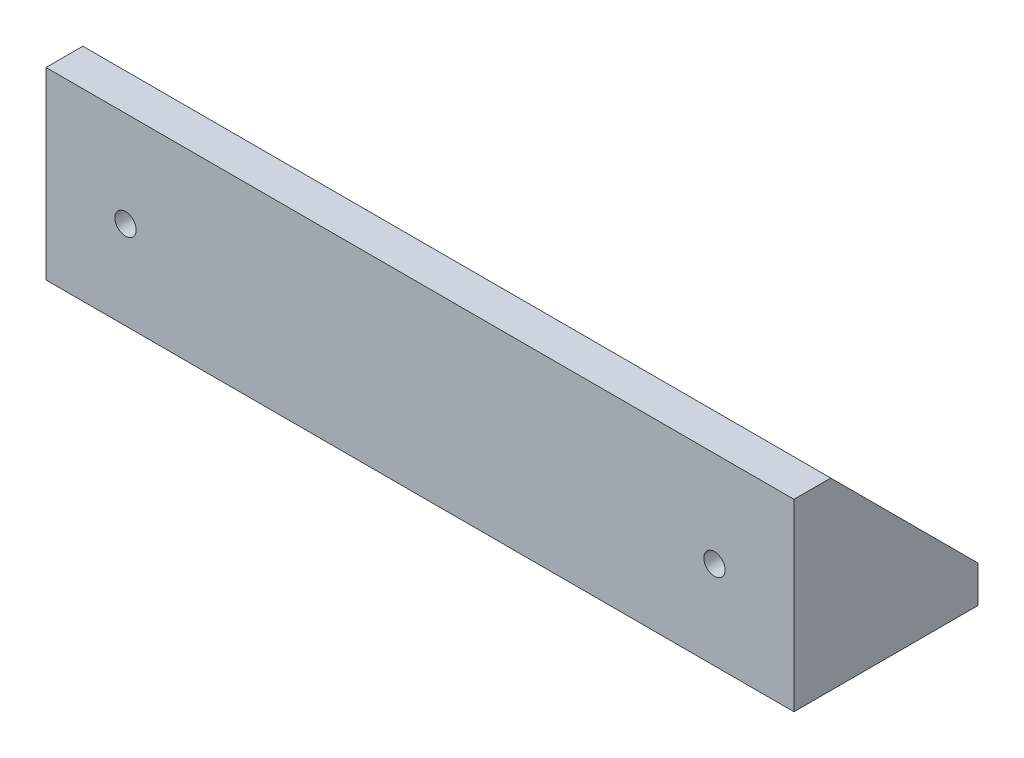
SolidWorks part; units mm, degrees
ref_plane "Front Plane" through (0, 0, 0) normal (0, 0, 1) x (1, 0, 0)
ref_plane "Top Plane" through (0, 0, 0) normal (0, 1, 0) x (1, 0, 0)
ref_plane "Right Plane" through (0, 0, 0) normal (1, 0, 0) x (0, 0, -1)
sketch "Sketch1" plane through (0, 0, 0) normal (1, 0, 0) x (0, 0, -1)
  line L0 (0, 25) -> (0, 0)
  line L1 (0, 0) -> (25, 0)
  line L2 (25, 0) -> (25, 5)
  line L3 (25, 5) -> (5, 25)
  line L4 (5, 25) -> (0, 25)
  point P3 (0, 0)
  point P7 (0, 0)
  dimension "D1" = 25
  dimension "D2" = 5
extrude "Boss-Extrude1" add sketch "Sketch1" along normal blind 101.6 from offset 50.8 offset against normal yes
sketch "Sketch3" plane through (0, 0, 0) normal (1, 0, 0) x (0, 0, -1)
  line L1 (5, 25) -> (25, 25)
  line L2 (5, 25) -> (5, 5)
  line L3 (5, 5) -> (25, 5)
  line L4 (25, 25) -> (25, 5)
  point P4 (0, 0)
  point P5 (0, 0)
  point P8 (0, 0)
  point P9 (0, 0)
  point P11 (0, 0)
  point P12 (0, 0)
  point P14 (0, 0)
  point P15 (0, 0)
  point P16 (0, 0)
  point P17 (0, 0)
  point P18 (0, 0)
  point P19 (0, 0)
  point P21 (0, 0)
extrude "hollow" cut sketch "Sketch3" against normal blind 90 from offset 45
hole_wizard "bottom holes" positions "Sketch4" profile "Sketch5" hole size "M2.5" standard "ISO" end condition through all
sketch "Sketch4" plane through (0, 0, 0) normal (0, -1, 0) x (-1, 0, 0)
  line L1 (0, 0) -> (0, 25) construction
  line L3 (-50.8, 0) -> (50.8, 0) construction
  point P0 (40, 12)
  point P12 (-40, 12)
  dimension "D1" = 40
  dimension "D2" = 12
sketch "Sketch5" plane through (-40, 0, -12) normal (1, 0, 0) x (0, 0, -1)
  line L0 (0, 0) -> (0, 25)
  line L1 (0, 25) -> (1.45, 25)
  line L2 (1.45, 25) -> (1.45, 0)
  line L5 (1.45, 0) -> (0, 0)
  line L11 (0, -6.35) -> (0, 107.95) construction
  dimension "Thru Hole Dia." = 2.9
  dimension "Thru Hole Depth" = 25
hole_wizard "front holes" positions "Sketch6" profile "Sketch7" hole size "M2.5" standard "ISO" end condition through all
sketch "Sketch6" plane through (0, 0, 0) normal (0, 0, 1) x (1, 0, 0)
  line L0 (0, 25) -> (0, 0) construction
  line L1 (50.8, 0) -> (-50.8, 0) construction
  line L2 (0, 0) -> (0, 25) construction
  point P0 (-40, 12)
  point P12 (40, 12)
  dimension "D1" = 40
  dimension "D2" = 12
sketch "Sketch7" plane through (-40, 12, 0) normal (1, 0, 0) x (0, -1, 0)
  line L0 (0, 0) -> (0, 25)
  line L1 (0, 25) -> (1.45, 25)
  line L2 (1.45, 25) -> (1.45, 0)
  line L5 (1.45, 0) -> (0, 0)
  line L11 (0, -6.35) -> (0, 107.95) construction
  dimension "Thru Hole Dia." = 2.9
  dimension "Thru Hole Depth" = 25
